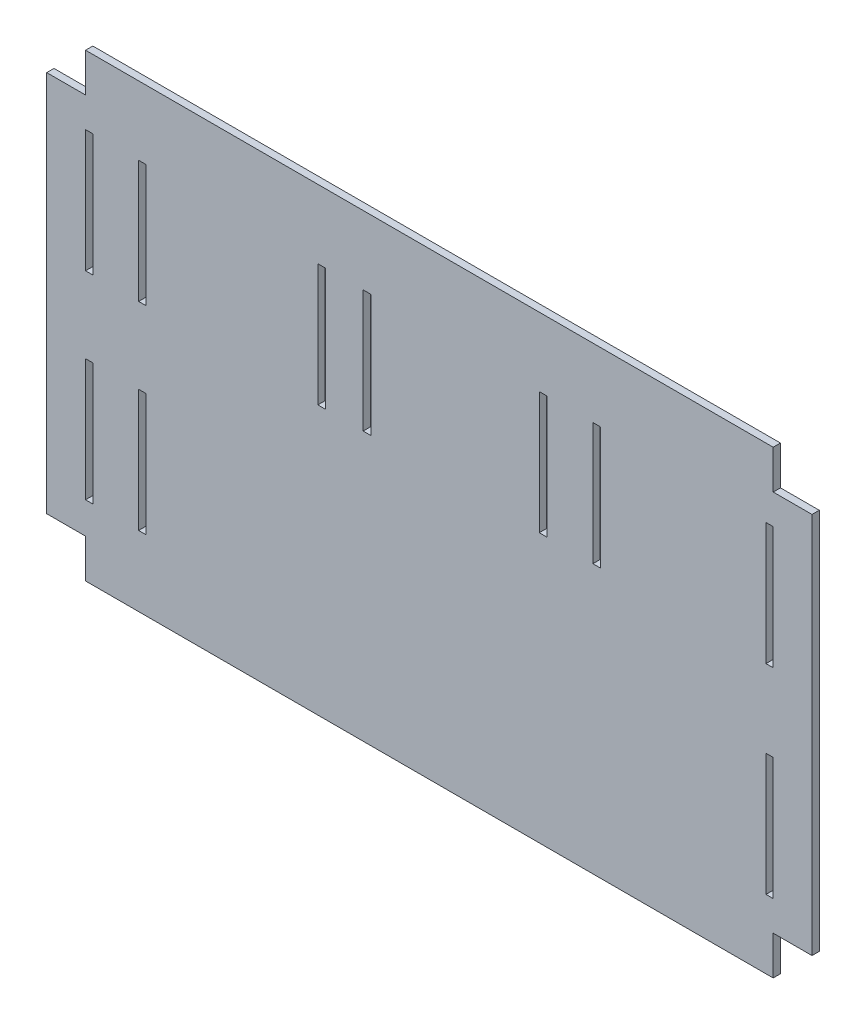
SolidWorks part; units mm, degrees
ref_plane "前基準面" through (0, 0, 0) normal (0, 0, 1) x (1, 0, 0)
ref_plane "上基準面" through (0, 0, 0) normal (0, 1, 0) x (1, 0, 0)
ref_plane "右基準面" through (0, 0, 0) normal (1, 0, 0) x (0, 0, -1)
sketch "草圖1" plane through (0, 0, 0) normal (0, 0, 1) x (1, 0, 0)
  line L1 (-250.4, 150.4) -> (250.4, 150.4)
  line L2 (-250.4, 150.4) -> (-250.4, -150.4)
  line L3 (-250.4, -150.4) -> (250.4, -150.4)
  line L4 (250.4, 150.4) -> (250.4, -150.4)
  line L5 (-250.4, 150.4) -> (250.4, -150.4) construction
  line L6 (-250.4, -150.4) -> (250.4, 150.4) construction
  point P0 (0, 0)
  dimension "D1" = 500.8
  dimension "D2" = 300.8
extrude "填料-伸長1" add sketch "草圖1" along normal blind 4.75 contours L1 L4 L3 L2
sketch "草圖2" plane through (0, 0, 0) normal (0, 0, -1) x (-1, 0, 0)
  line L0 (-225, 125) -> (-225, -125) construction
  line L1 (-250.4, 150.4) -> (-225, 150.4)
  line L2 (-250.4, 150.4) -> (-250.4, 125)
  line L3 (-250.4, 125) -> (-225, 125)
  line L4 (-225, 150.4) -> (-225, 125)
  line L5 (-250.4, -150.4) -> (-225, -150.4)
  line L6 (-250.4, -150.4) -> (-250.4, -125)
  line L7 (-250.4, -125) -> (-225, -125)
  line L8 (-225, -150.4) -> (-225, -125)
  line L9 (250.4, 150.4) -> (225, 150.4)
  line L10 (250.4, 150.4) -> (250.4, 125)
  line L11 (250.4, 125) -> (225, 125)
  line L12 (225, 150.4) -> (225, 125)
  line L13 (250.4, -150.4) -> (225, -150.4)
  line L14 (250.4, -150.4) -> (250.4, -125)
  line L15 (250.4, -125) -> (225, -125)
  line L16 (225, -150.4) -> (225, -125)
  line L17 (225, 125) -> (225, -125) construction
  line L18 (250.4, 150.4) -> (-250.4, 150.4) construction
  line L19 (-225, 105.4) -> (-220.25, 105.4)
  line L20 (-225, 105.4) -> (-225, 25.4)
  line L21 (-225, 25.4) -> (-220.25, 25.4)
  line L22 (-220.25, 105.4) -> (-220.25, 25.4)
  line L23 (-225, -25.4) -> (-220.25, -25.4)
  line L24 (-225, -25.4) -> (-225, -105.4)
  line L25 (-225, -105.4) -> (-220.25, -105.4)
  line L26 (-220.25, -25.4) -> (-220.25, -105.4)
  line L27 (250.4, -150.4) -> (-250.4, -150.4) construction
  line L29 (225, 105.4) -> (220.25, 105.4)
  line L30 (225, 105.4) -> (225, 25.4)
  line L31 (225, 25.4) -> (220.25, 25.4)
  line L32 (220.25, 105.4) -> (220.25, 25.4)
  line L33 (225, -24.4) -> (220.25, -24.4)
  line L34 (225, -24.4) -> (225, -104.4)
  line L35 (225, -104.4) -> (220.25, -104.4)
  line L36 (220.25, -24.4) -> (220.25, -104.4)
  line L44 (190.25, 105.4) -> (190.25, 25.4)
  line L45 (190.25, 105.4) -> (185.5, 105.4)
  line L46 (185.5, 105.4) -> (185.5, 25.4)
  line L47 (190.25, 25.4) -> (185.5, 25.4)
  line L48 (190.25, -24.4) -> (190.25, -104.4)
  line L49 (190.25, -24.4) -> (185.5, -24.4)
  line L50 (185.5, -24.4) -> (185.5, -104.4)
  line L51 (190.25, -104.4) -> (185.5, -104.4)
  line L52 (-112.1137, 105.4) -> (-112.1137, 25.4)
  line L53 (-112.1137, 25.4) -> (-107.0171, 25.4)
  line L54 (-107.0171, 105.4) -> (-107.0171, 25.4)
  line L55 (-112.1137, 105.4) -> (-107.0171, 105.4)
  line L60 (-77.0171, 105.4) -> (-77.0171, 25.4)
  line L61 (-77.0171, 25.4) -> (-71.9205, 25.4)
  line L62 (-71.9205, 105.4) -> (-71.9205, 25.4)
  line L63 (-77.0171, 105.4) -> (-71.9205, 105.4)
  line L68 (38.2329, 105.4) -> (38.2329, 25.4)
  line L69 (38.2329, 25.4) -> (43.3295, 25.4)
  line L70 (43.3295, 105.4) -> (43.3295, 25.4)
  line L71 (38.2329, 105.4) -> (43.3295, 105.4)
  line L80 (67.8863, 105.4) -> (67.8863, 25.4)
  line L81 (67.8863, 25.4) -> (72.9829, 25.4)
  line L82 (72.9829, 105.4) -> (72.9829, 25.4)
  line L83 (67.8863, 105.4) -> (72.9829, 105.4)
  line L84 (-250.4, 0) -> (250.4, 0) construction
  line L85 (-250.4, 150.4) -> (-250.4, -150.4) construction
  line L86 (250.4, 150.4) -> (250.4, -150.4) construction
  dimension "D1" = 25.4
  dimension "D2" = 25.4
  dimension "D3" = 25.4
  dimension "D4" = 25.4
  dimension "D5" = 25.4
  dimension "D6" = 25.4
  dimension "D7" = 25.4
  dimension "D8" = 25.4
  dimension "D9" = 4.75
  dimension "D10" = 80
  dimension "D11" = 45
  dimension "D12" = 4.75
  dimension "D13" = 80
  dimension "D14" = 45
  dimension "D15" = 4.75
  dimension "D16" = 4.75
  dimension "D17" = 80
  dimension "D18" = 80
  dimension "D19" = 46
  dimension "D20" = 45
  dimension "D27" = 34.75
  dimension "D23" = 30
  dimension "D28" = 30
  dimension "D29" = 112.8863
  dimension "D30" = 115.25
  dimension "D22" = 2
  dimension "D24" = 2
  dimension "D25" = 2
  dimension "D26" = 2
extrude "除料-伸長1" cut sketch "草圖2" against normal blind 10
